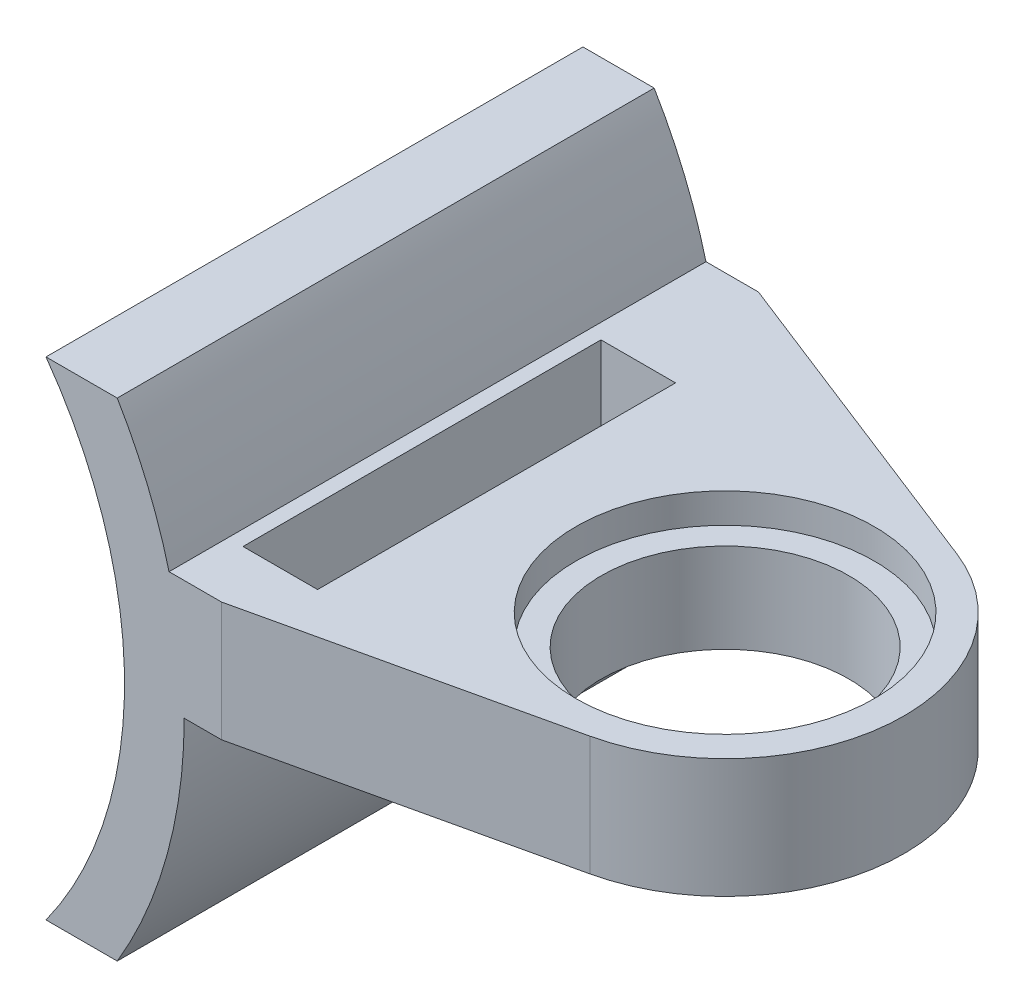
SolidWorks part; units mm, degrees
ref_plane "Front Plane" through (0, 0, 0) normal (0, 0, 1) x (1, 0, 0)
ref_plane "Top Plane" through (0, 0, 0) normal (0, 1, 0) x (1, 0, 0)
ref_plane "Right Plane" through (0, 0, 0) normal (1, 0, 0) x (0, 0, -1)
sketch "草图1" plane through (0, 0, 0) normal (0, 0, 1) x (1, 0, 0)
  line L6 (13.755, 8.1732) -> (11.3666, 8.1732)
  line L7 (11.3666, -8.1732) -> (13.755, -8.1732)
  arc A0 (11.3666, 8.1732) -> (11.3666, -8.1732) centre (0, 0) cw
  arc A1 (13.755, 8.1732) -> (13.755, -8.1732) centre (0, 0) cw
  dimension "D1" = 14
  dimension "D2" = 16
extrude "凸台-拉伸1" add sketch "草图1" along normal blind 18
sketch "草图3" plane through (0, 0, 0) normal (0, 1, 0) x (1, 0, 0)
  line L1 (17.25, -18) -> (14.8775, -18)
  line L2 (28.1863, -4.2791) -> (17.25, 0)
  line L4 (17.25, -18) -> (27.3252, -15.7185)
  line L5 (13.755, -18) -> (16, -18) construction
  line L6 (16, -18) -> (16, 0) construction
  line L7 (14.8775, -18) -> (14.8775, 0)
  line L8 (16, 0) -> (13.755, 0) construction
  line L9 (14.8775, 0) -> (17.25, 0)
  line L10 (16, -18) -> (16, 0) construction
  line L12 (16, -16.0286) -> (18.5, -16.0286)
  line L13 (16, -16.0286) -> (16, -4.0286)
  line L14 (16, -4.0286) -> (18.5, -4.0286)
  line L15 (18.5, -16.0286) -> (18.5, -4.0286)
  line L16 (16, -16.0286) -> (18.5, -4.0286) construction
  line L17 (16, -4.0286) -> (18.5, -16.0286) construction
  arc A0 (28.1863, -4.2791) -> (27.3252, -15.7185) centre (26, -9.8666) cw
  circle A1 centre (26, -9.8666) radius 4.15
  point P14 (26, -10.0286)
  point P16 (17.25, -10.0286)
  dimension "D2" = 6
  dimension "D3" = 8.3
  dimension "D4" = 12
  dimension "D5" = 2.5
  dimension "4.5" = 10
extrude "凸台-拉伸2" add sketch "草图3" along normal blind 4
sketch "草图4" plane through (0, 4, 0) normal (0, 1, 0) x (1, 0, 0)
  circle A0 centre (26, -9.8666) radius 5
  dimension "D1" = 10
extrude "切除-拉伸1" cut sketch "草图4" against normal blind 1
